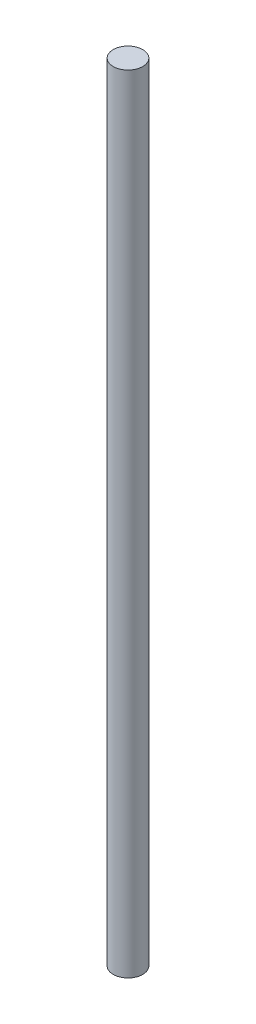
SolidWorks part; units mm, degrees
ref_plane "Front Plane" through (0, 0, 0) normal (0, 0, 1) x (1, 0, 0)
ref_plane "Top Plane" through (0, 0, 0) normal (0, 1, 0) x (1, 0, 0)
ref_plane "Right Plane" through (0, 0, 0) normal (1, 0, 0) x (0, 0, -1)
sketch "Sketch1" plane through (0, 0, 0) normal (0, 1, 0) x (1, 0, 0)
  circle A0 centre (0, 0) radius 37.5
  dimension "D1" = 75
extrude "Boss-Extrude1" add sketch "Sketch1" along normal blind 2000
